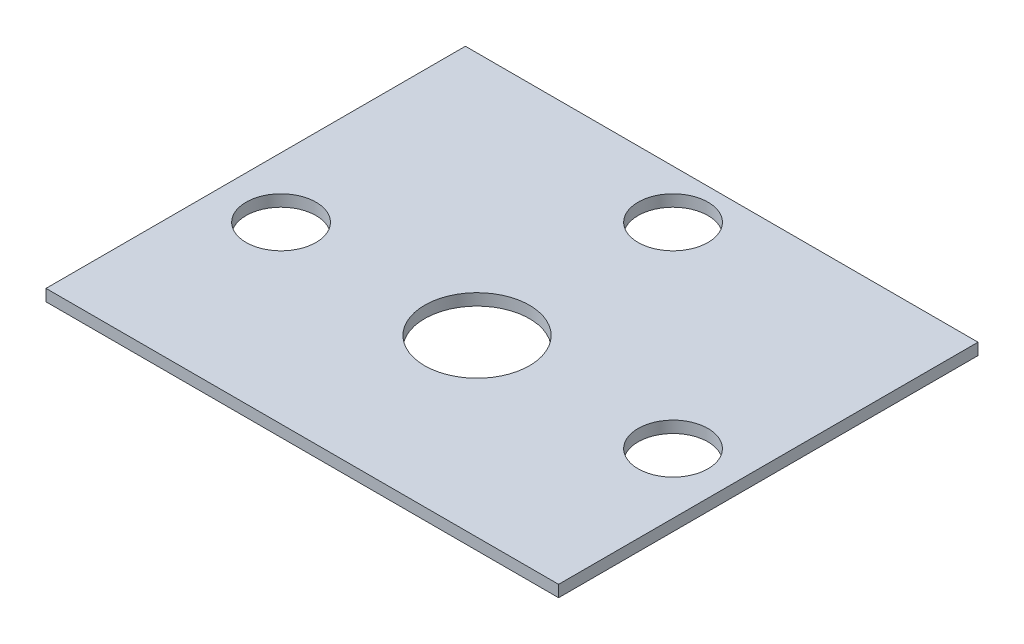
SolidWorks part; units mm, degrees
material "6061 Alloy"
ref_plane "Front Plane" through (0, 0, 0) normal (0, 0, 1) x (1, 0, 0)
ref_plane "Top Plane" through (0, 0, 0) normal (0, 1, 0) x (1, 0, 0)
ref_plane "Right Plane" through (0, 0, 0) normal (1, 0, 0) x (0, 0, -1)
sketch "Sketch1" plane through (0, 0, 0) normal (0, 1, 0) x (1, 0, 0)
  line L7 (-69.85, -57.15) -> (69.85, -57.15)
  line L8 (-69.85, -57.15) -> (-69.85, 57.15)
  line L9 (-69.85, 57.15) -> (69.85, 57.15)
  line L10 (69.85, -57.15) -> (69.85, 57.15)
  line L11 (-69.85, -57.15) -> (69.85, 57.15) construction
  line L12 (-69.85, 57.15) -> (69.85, -57.15) construction
  circle A2 centre (0, 43.8912) radius 9.525
  circle A3 centre (-53.4162, -9.525) radius 9.525
  circle A4 centre (53.4162, -9.525) radius 9.525
  circle A5 centre (0, -9.525) radius 14.2875
  circle A6 centre (0, -9.525) radius 53.4162 construction
  point P0 (0, 0)
  dimension "D3" = 28.575
  dimension "D4" = 9.525
  dimension "D5" = 19.05
  dimension "D6" = 19.05
  dimension "D7" = 19.05
  dimension "D8" = 106.8324
  dimension "D1" = 139.7
  dimension "D2" = 114.3
extrude "Boss-Extrude1" add sketch "Sketch1" along normal mid plane 3.175
hole_wizard "#10 Clearance Hole1" [suppressed] positions "Sketch3" profile "Sketch4" hole size "#10" standard "ANSI Inch"
sketch "Sketch3" plane through (0, 1.5875, 0) normal (0, 1, 0) x (1, 0, 0)
  circle A0 centre (53.4162, -9.525) radius 9.525 construction
  circle A1 centre (0, 43.8912) radius 9.525 construction
  circle A2 centre (-53.4162, -9.525) radius 9.525 construction
  circle A3 centre (53.4162, -9.525) radius 9.525
  circle A4 centre (0, 43.8912) radius 9.525
  circle A5 centre (-53.4162, -9.525) radius 9.525
  circle A6 centre (-53.4162, -9.525) radius 25.4 construction
  circle A7 centre (0, 43.8912) radius 25.4 construction
  circle A8 centre (53.4162, -9.525) radius 25.4 construction
  point P0 (-53.4162, 15.875)
  point P16 (-53.4162, -34.925)
  point P22 (-25.4, 43.8912)
  point P24 (25.4, 43.8912)
  point P29 (53.4162, 15.875)
  point P31 (53.4162, -34.925)
  dimension "D1" = 50.8
  dimension "D2" = 50.8
  dimension "D3" = 50.8
sketch "Sketch4" plane through (-53.4162, 1.5875, -15.875) normal (1, 0, 0) x (0, 0, 1)
  line L0 (0, 0) -> (0, 3.175)
  line L1 (0, 3.175) -> (2.5527, 3.175)
  line L2 (2.5527, 3.175) -> (2.5527, 0)
  line L5 (2.5527, 0) -> (0, 0)
  line L11 (0, -6.35) -> (0, 107.95) construction
  dimension "Thru Hole Dia." = 5.1054
  dimension "Thru Hole Depth" = 3.175
hole_wizard "1/4 Clearance Hole1" [suppressed] positions "Sketch5" profile "Sketch6" hole size "1/4" standard "ANSI Inch"
sketch "Sketch5" [suppressed] plane through (0, 1.5875, 0) normal (0, 1, 0) x (1, 0, 0)
  line L0 (25.4, 43.8912) -> (53.4162, 15.875) construction
  line L2 (-25.4, 43.8912) -> (-53.4162, 15.875) construction
  circle A0 centre (0, -9.525) radius 14.2875 construction
  circle A1 centre (0, -9.525) radius 14.2875
  circle A2 centre (-53.4162, 15.875) radius 2.5527 construction
  circle A3 centre (-25.4, 43.8912) radius 2.5527 construction
  circle A4 centre (25.4, 43.8912) radius 2.5527 construction
  circle A5 centre (53.4162, 15.875) radius 2.5527 construction
  circle A6 centre (-53.4162, 15.875) radius 2.5527
  circle A7 centre (-25.4, 43.8912) radius 2.5527
  circle A8 centre (25.4, 43.8912) radius 2.5527
  circle A9 centre (53.4162, 15.875) radius 2.5527
  point P0 (-39.4081, 29.8831)
  point P13 (39.4081, 29.8831)
  point P15 (-39.4081, -47.625)
  point P17 (39.4081, -47.625)
  point P38 (39.4081, 29.8831)
  point P39 (-39.4081, 29.8831)
  point P40 (0, 0)
  point P41 (0, 0)
  dimension "D3" = 38.1
sketch "Sketch6" plane through (-39.4081, 1.5875, -29.8831) normal (1, 0, 0) x (0, 0, 1)
  line L0 (0, 0) -> (0, 3.175)
  line L1 (0, 3.175) -> (3.3782, 3.175)
  line L2 (3.3782, 3.175) -> (3.3782, 0)
  line L5 (3.3782, 0) -> (0, 0)
  line L11 (0, -6.35) -> (0, 107.95) construction
  dimension "Thru Hole Dia." = 6.7564
  dimension "Thru Hole Depth" = 3.175
chamfer "Chamfer1" [suppressed] distance 31.75 angle 45
fillet "Fillet2" [suppressed] radius 6.35
